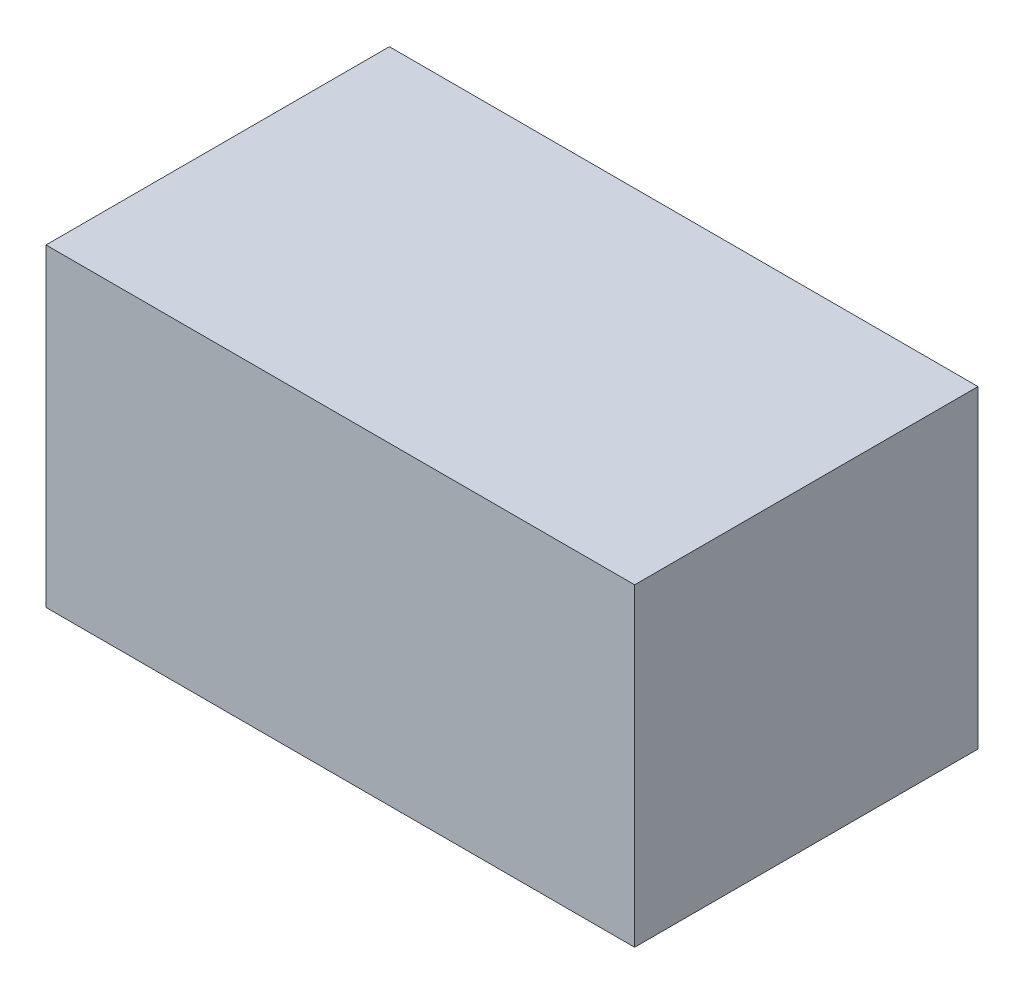
SolidWorks part; units mm, degrees
ref_plane "Front" through (0, 0, 0) normal (0, 0, 1) x (1, 0, 0)
ref_plane "Top" through (0, 0, 0) normal (0, 1, 0) x (1, 0, 0)
ref_plane "Right" through (0, 0, 0) normal (1, 0, 0) x (0, 0, -1)
sketch "Sketch1" plane through (0, 0, 0) normal (0, 0, 1) x (1, 0, 0)
  line L1 (0, 0) -> (18, 0)
  line L2 (0, 0) -> (0, -9.6)
  line L3 (0, -9.6) -> (18, -9.6)
  line L4 (18, 0) -> (18, -9.6)
  dimension "D1" = 18
  dimension "D2" = 9.6
extrude "Extrude1" add sketch "Sketch1" along normal blind 10.5
